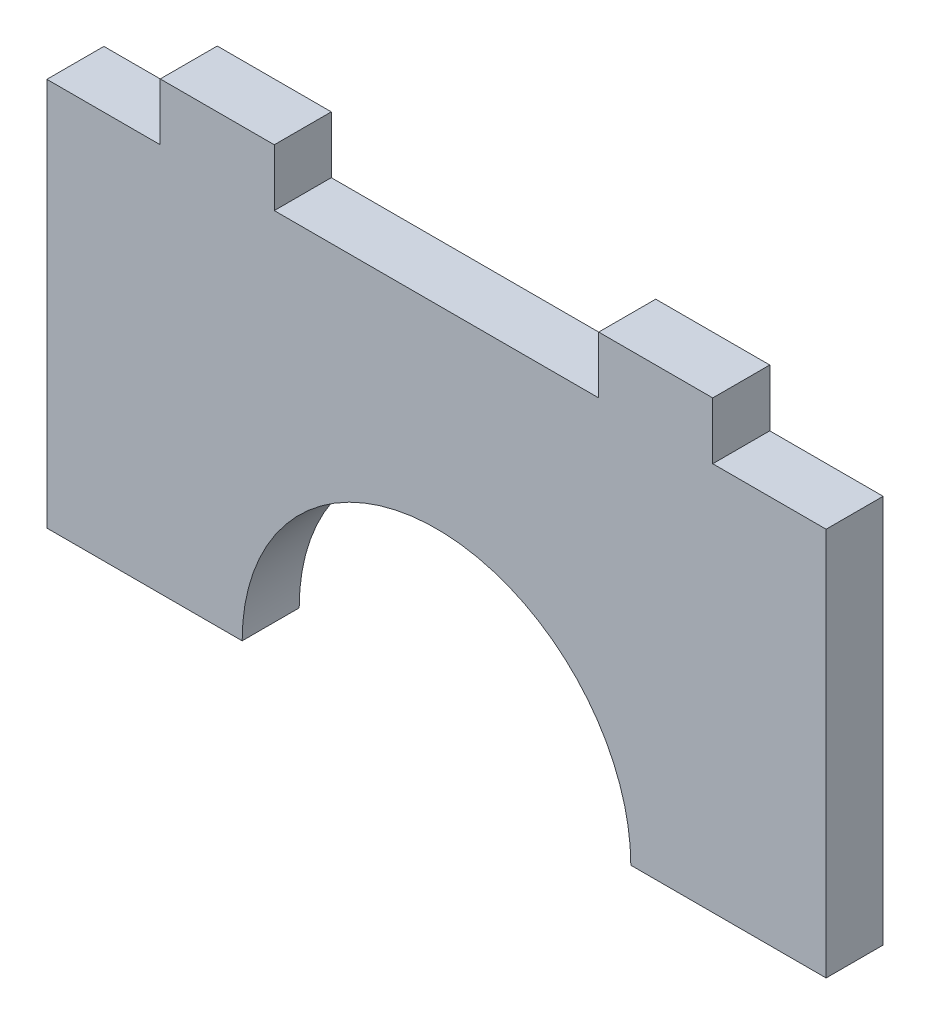
SolidWorks part; units mm, degrees
ref_plane "Front Plane" through (0, 0, 0) normal (0, 0, 1) x (1, 0, 0)
ref_plane "Top Plane" through (0, 0, 0) normal (0, 1, 0) x (1, 0, 0)
ref_plane "Right Plane" through (0, 0, 0) normal (1, 0, 0) x (0, 0, -1)
sketch "Sketch1" plane through (0, 0, 0) normal (0, 0, 1) x (1, 0, 0)
  line L0 (0, -10.225) -> (0, 10.225)
  line L1 (20.5, -10.225) -> (-20.5, -10.225)
  line L2 (20.5, -10.225) -> (20.5, 10.225)
  line L3 (20.5, 10.225) -> (-20.5, 10.225)
  line L4 (-20.5, -10.225) -> (-20.5, 10.225)
  line L5 (20.5, -10.225) -> (-20.5, 10.225) construction
  line L6 (20.5, 10.225) -> (-20.5, -10.225) construction
  line L7 (-14.535, 10.225) -> (-8.535, 10.225)
  line L8 (-14.535, 10.225) -> (-14.535, 13.225)
  line L9 (-14.535, 13.225) -> (-8.535, 13.225)
  line L10 (-8.535, 10.225) -> (-8.535, 13.225)
  line L11 (8.535, 10.225) -> (8.535, 13.225)
  line L12 (14.535, 13.225) -> (8.535, 13.225)
  line L13 (14.535, 10.225) -> (14.535, 13.225)
  line L14 (14.535, 10.225) -> (8.535, 10.225)
  circle A0 centre (0, -10.225) radius 10.225
  point P0 (0, 0)
  dimension "D1" = 6
  dimension "D2" = 3
  dimension "D3" = 20.45
  dimension "D4" = 41
  dimension "D5" = 8.535
extrude "Boss-Extrude1" add sketch "Sketch1" along normal blind 3 contours L4 L1 L0 L3 | L2 L3 L0 L1 | L3 L13 L12 L11 | L3 L10 L9 L8
